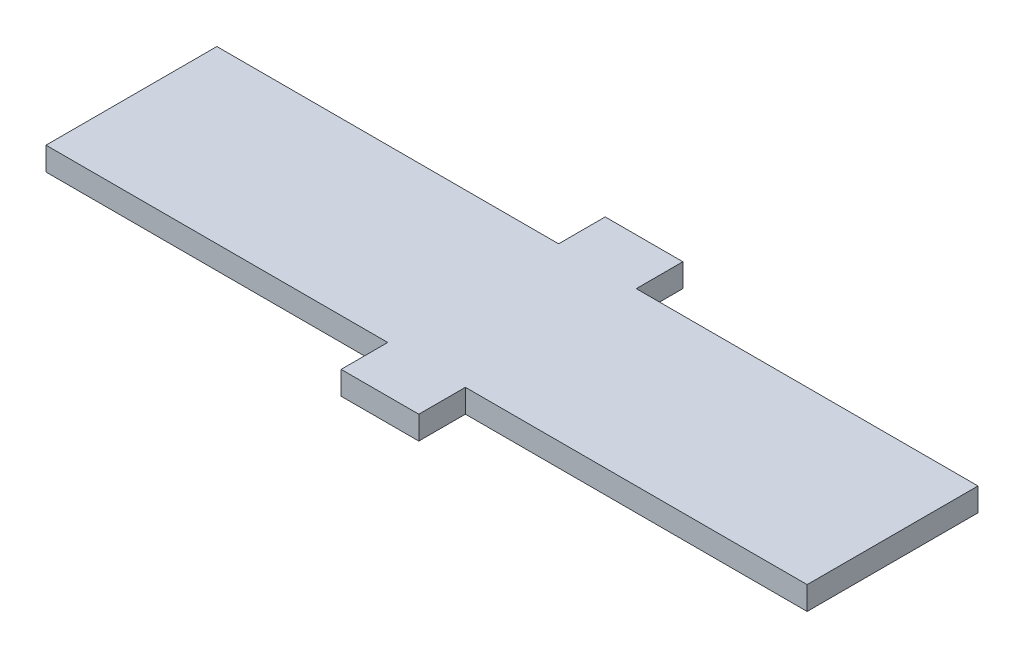
SolidWorks part; units mm, degrees
ref_plane "Plan de face" through (0, 0, 0) normal (0, 0, 1) x (1, 0, 0)
ref_plane "Plan de dessus" through (0, 0, 0) normal (0, 1, 0) x (1, 0, 0)
ref_plane "Plan de droite" through (0, 0, 0) normal (1, 0, 0) x (0, 0, -1)
sketch "Sketch1" plane through (0, 0, 0) normal (0, 1, 0) x (1, 0, 0)
  line L1 (-24.5, -5.5) -> (24.5, -5.5)
  line L2 (-24.5, -5.5) -> (-24.5, 5.5)
  line L3 (-24.5, 5.5) -> (24.5, 5.5)
  line L4 (24.5, -5.5) -> (24.5, 5.5)
  line L5 (-24.5, -5.5) -> (24.5, 5.5) construction
  line L6 (-24.5, 5.5) -> (24.5, -5.5) construction
  point P0 (0, 0)
  dimension "D1" = 49
  dimension "D2" = 11
extrude "Boss-Extrude1" add sketch "Sketch1" along normal blind 1.5
sketch "Sketch2" plane through (0, 1.5, 0) normal (0, 1, 0) x (1, 0, 0)
  line L0 (24.5, 5.5) -> (-24.5, 5.5) construction
  line L1 (-2.5, 5.5) -> (2.5, 5.5)
  line L2 (-2.5, 5.5) -> (-2.5, 8.5)
  line L3 (-2.5, 8.5) -> (2.5, 8.5)
  line L4 (2.5, 5.5) -> (2.5, 8.5)
  line L5 (-24.5, 5.5) -> (-24.5, -5.5) construction
  dimension "D1" = 5
  dimension "D2" = 3
  dimension "D3" = 22
extrude "Boss-Extrude2" add sketch "Sketch2" against normal blind 1.5
sketch "Sketch3" plane through (0, 1.5, 0) normal (0, 1, 0) x (1, 0, 0)
  line L0 (-24.5, -5.5) -> (24.5, -5.5) construction
  line L1 (-2.5, -5.5) -> (2.5, -5.5)
  line L2 (-2.5, -5.5) -> (-2.5, -8.5)
  line L3 (-2.5, -8.5) -> (2.5, -8.5)
  line L4 (2.5, -5.5) -> (2.5, -8.5)
  line L5 (-24.5, 5.5) -> (-24.5, -5.5) construction
  dimension "D1" = 3
  dimension "D2" = 5
  dimension "D3" = 22
extrude "Boss-Extrude3" add sketch "Sketch3" against normal blind 1.5
